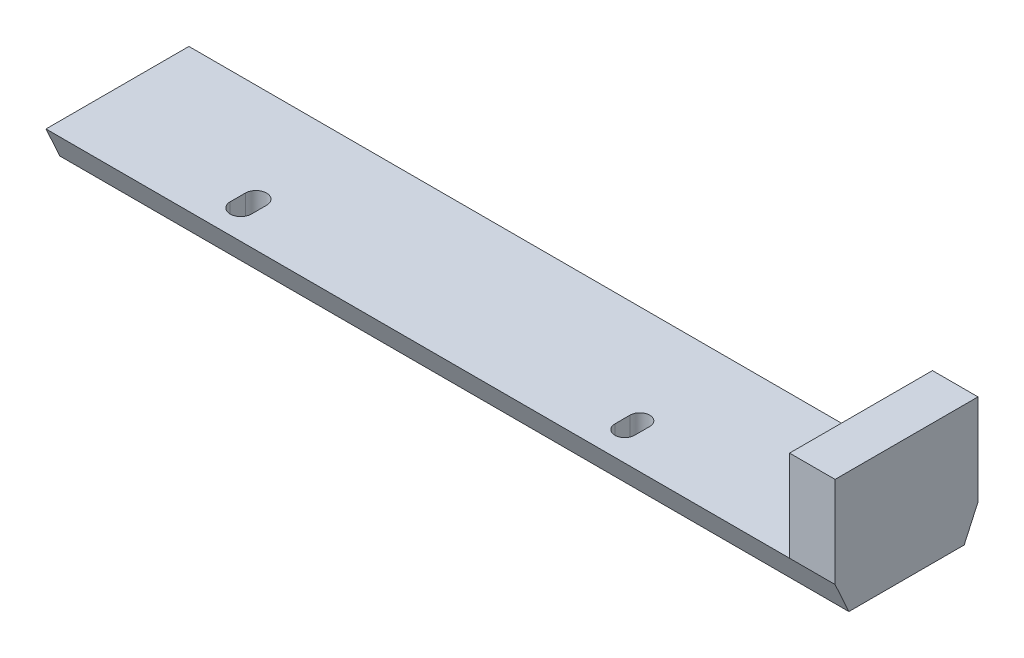
SolidWorks part; units mm, degrees
other "标注1"
sketch "草图3" plane through (-22.25, 4, -10) normal (-0.231, 0.6469, -0.7268) x (-0.9696, -0.2151, 0.1167)
other "标注2"
sketch "草图4" plane through (22.25, 8, -30) normal (0.0083, 0.0567, -0.9984) x (-0.9991, 0.0415, -0.0059)
ref_plane "前视基准面" through (0, 0, 0) normal (0, 0, 1) x (1, 0, 0)
ref_plane "上视基准面" through (0, 0, 0) normal (0, 1, 0) x (1, 0, 0)
ref_plane "右视基准面" through (0, 0, 0) normal (1, 0, 0) x (0, 0, -1)
other "Configuration Table"
sketch "草图1" plane through (0, 0, 0) normal (0, 1, 0) x (1, 0, 0)
  line L36 (0, -10) -> (52, -10)
  line L37 (0, -10) -> (0, 0)
  line L38 (0, 0) -> (52, 0)
  line L39 (52, -10) -> (52, 0)
  dimension "D1" = 10
  dimension "D2" = 52
extrude "凸台-拉伸1" add sketch "草图1" along normal blind 2
sketch "草图5" plane through (0, 2, 0) normal (0, 1, 0) x (1, 0, 0)
  line L2 (52, 0) -> (0, 0) construction
  line L3 (0, 0) -> (0, -10) construction
  circle A1 centre (36.2264, -2.7) radius 0.6
  circle A2 centre (10.9264, -2.7) radius 0.6
  dimension "D3" = 2.7
  dimension "D2" = 1.2
  dimension "D1" = 25.3
  dimension "D4" = 10.9264
extrude "切除-拉伸1" cut sketch "草图5" against normal through all
sketch "草图6" plane through (0, 2, 0) normal (0, 1, 0) x (1, 0, 0)
  line L0 (52, -10) -> (52, 0) construction
  line L1 (52, 0) -> (49, 0)
  line L2 (52, 0) -> (52, -10)
  line L3 (52, -10) -> (49, -10)
  line L4 (49, 0) -> (49, -10)
  line L5 (52, 0) -> (0, 0) construction
  line L6 (0, -10) -> (52, -10) construction
  dimension "D1" = 3
extrude "凸台-拉伸2" add sketch "草图6" along normal blind 6
sketch "草图7" plane through (0, 2, 0) normal (0, 1, 0) x (1, 0, 0)
  line L0 (10.9264, -2.2) -> (10.9264, -3.2) construction
  line L1 (11.6264, -2.2) -> (11.6264, -3.2)
  line L2 (10.2264, -2.2) -> (10.2264, -3.2)
  line L3 (36.2264, -2.2) -> (36.2264, -3.2) construction
  line L4 (36.8764, -2.2) -> (36.8764, -3.2)
  line L5 (35.5764, -2.2) -> (35.5764, -3.2)
  arc A0 (11.6264, -2.2) -> (10.2264, -2.2) centre (10.9264, -2.2) ccw
  arc A1 (10.2264, -3.2) -> (11.6264, -3.2) centre (10.9264, -3.2) ccw
  circle A3 centre (10.9264, -2.7) radius 0.6 construction
  arc A4 (36.8764, -2.2) -> (35.5764, -2.2) centre (36.2264, -2.2) ccw
  arc A5 (35.5764, -3.2) -> (36.8764, -3.2) centre (36.2264, -3.2) ccw
  circle A6 centre (36.2264, -2.7) radius 0.6 construction
  point P2 (10.9264, -2.7)
  point P7 (36.2264, -2.7)
  dimension "D1" = 1.4
  dimension "D2" = 1
  dimension "D3" = 1.3
extrude "切除-拉伸2" cut sketch "草图7" against normal through all
sketch "草图8" plane through (0, 2, 0) normal (0, 1, 0) x (1, 0, 0)
  line L0 (36.2264, -1.55) -> (36.2264, -3.85)
  arc A0 (36.8764, -2.2) -> (35.5764, -2.2) centre (36.2264, -2.2) ccw construction
  arc A1 (35.5764, -3.2) -> (36.8764, -3.2) centre (36.2264, -3.2) ccw construction
ref_plane "基准面1" through (36.2264, 0, 0) normal (1, 0, 0) x (0, 0, -1)
sketch "草图9" plane through (52, 0, 0) normal (1, 0, 0) x (0, 0, -1)
  line L0 (-0.2909, 2) -> (-1.2, 0)
  line L1 (0, 2) -> (-10, 2) construction
  line L2 (0, 0) -> (-10, 0) construction
  line L3 (-1.2, 0) -> (0, 0)
  line L4 (0, 0) -> (0, 8)
  line L7 (-9.7091, 2) -> (-8.8, 0)
  line L8 (-8.8, 0) -> (-10, 0)
  line L9 (-10, 2) -> (-10, 0) construction
  line L10 (-10, 0) -> (-10, 8)
  line L12 (-10, 8) -> (-9.7091, 8)
  line L13 (-10, 8) -> (0, 8) construction
  line L14 (-9.7091, 8) -> (-9.7091, 2)
  line L15 (-0.2909, 2) -> (-0.2909, 8)
  line L16 (-0.2909, 8) -> (0, 8)
  line L17 (0, 8) -> (0, 0) construction
  dimension "D1" = 1.2
  dimension "D2" = 0.2909
extrude "切除-拉伸3" cut sketch "草图9" against normal through all both
mirror "镜向1" about plane through (0, 0, 0) normal (0, 0, 1) of bodies 245
sketch "草图10" plane through (0, 0, 0) normal (0, 0, 1) x (1, 0, 0)
  line L1 (-2.5208, 8.3928) -> (52.5885, 8.3928)
  line L2 (-2.5208, 8.3928) -> (-2.5208, -2.8146)
  line L3 (-2.5208, -2.8146) -> (52.5885, -2.8146)
  line L4 (52.5885, 8.3928) -> (52.5885, -2.8146)
extrude "切除-拉伸4" cut sketch "草图10" along normal through all
